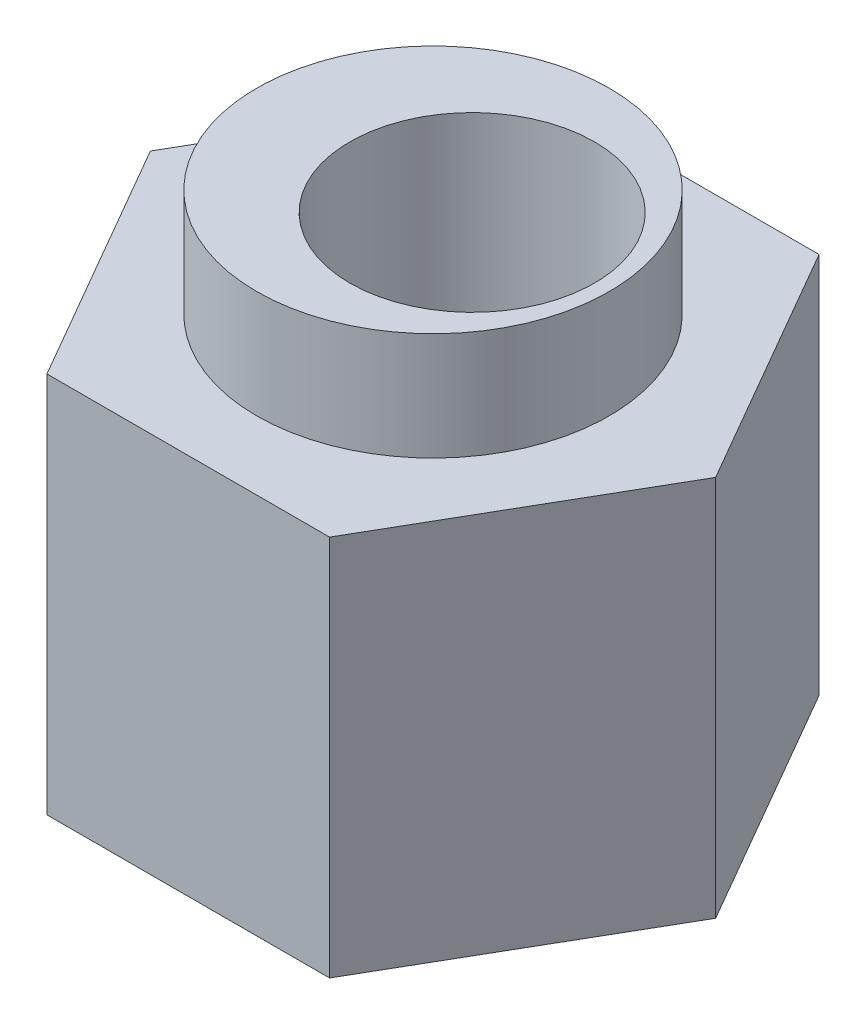
SolidWorks part; units mm, degrees
ref_plane "Front Plane" through (0, 0, 0) normal (0, 0, 1) x (1, 0, 0)
ref_plane "Top Plane" through (0, 0, 0) normal (0, 1, 0) x (1, 0, 0)
ref_plane "Right Plane" through (0, 0, 0) normal (1, 0, 0) x (0, 0, -1)
sketch "Sketch1" plane through (0, 0, 0) normal (0, 1, 0) x (1, 0, 0)
  line L1 (5.7735, 0) -> (2.8868, 5)
  line L2 (2.8868, 5) -> (-2.8868, 5)
  line L3 (-2.8868, 5) -> (-5.7735, 0)
  line L4 (-5.7735, 0) -> (-2.8868, -5)
  line L5 (-2.8868, -5) -> (2.8868, -5)
  line L6 (2.8868, -5) -> (5.7735, 0)
  circle A0 centre (0, 0) radius 3.6 construction
  circle A1 centre (0, 0) radius 5 construction
extrude "Boss-Extrude1" add sketch "Sketch1" along normal blind 7.8
sketch "Sketch2" plane through (0, 7.8, 0) normal (0, 1, 0) x (1, 0, 0)
  circle A1 centre (0, 0) radius 3.6 construction
  circle A2 centre (0, 0) radius 3.6
extrude "Boss-Extrude2" add sketch "Sketch2" along normal blind 2.2
sketch "Sketch3" plane through (0, 0, 0) normal (0, -1, 0) x (1, 0, 0)
  circle A1 centre (0, 0) radius 3.6
  circle A2 centre (0, 0) radius 3.6
  dimension "D1" = 0
extrude "Boss-Extrude3" add sketch "Sketch3" along normal blind 0.4
sketch "Sketch4" plane through (0, 0, 0) normal (0, 1, 0) x (1, 0, 0)
  line L0 (3.6, 0) -> (3.3, 0) construction
  line L1 (3.3, 0) -> (-1.7, 0) construction
  circle A0 centre (0, 0) radius 3.6 construction
  circle A1 centre (0.8, 0) radius 2.5
extrude "Cut-Extrude1" cut sketch "Sketch4" against normal through all and the other way through all
